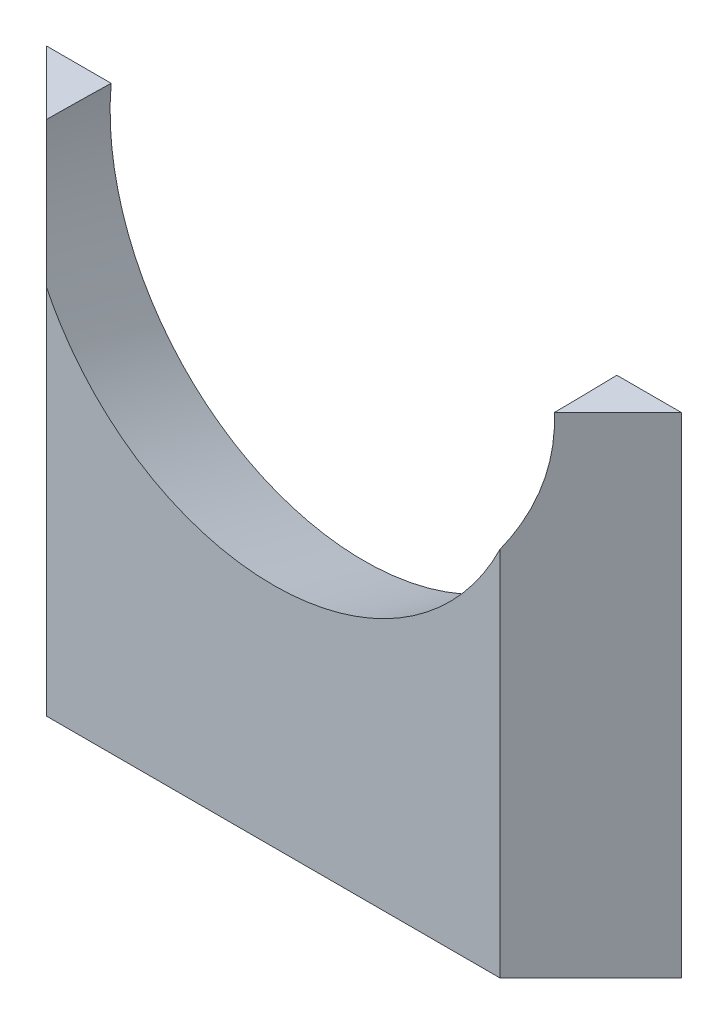
SolidWorks part; units mm, degrees
ref_plane "Front Plane" through (0, 0, 0) normal (0, 0, 1) x (1, 0, 0)
ref_plane "Top Plane" through (0, 0, 0) normal (0, 1, 0) x (1, 0, 0)
ref_plane "Right Plane" through (0, 0, 0) normal (1, 0, 0) x (0, 0, -1)
sketch "Sketch1" plane through (0, 0, 0) normal (0, 1, 0) x (1, 0, 0)
  line L0 (-17.5, 2.5) -> (17.5, 2.5)
  line L1 (17.5, 2.5) -> (12.5, -2.5)
  line L2 (12.5, -2.5) -> (-12.5, -2.5)
  line L3 (-12.5, -2.5) -> (-17.5, 2.5)
  line L4 (0, 2.5) -> (0, 0) construction
  line L5 (0, 0) -> (0, -2.5) construction
  dimension "D1" = 2.5
  dimension "D2" = 2.5
  dimension "D3" = 35
  dimension "D4" = 25
extrude "Boss-Extrude1" add sketch "Sketch1" along normal blind 27
ref_plane "Plane1" through (0, 0.625, 2.3325) normal (0, 0.2588, 0.9659) x (1, 0, 0)
sketch "Sketch2" plane through (0, 0.625, 2.3325) normal (0, 0.2588, 0.9659) x (1, 0, 0)
  line L0 (-12.5, 25.4329) -> (12.5, 25.4329) construction
  circle A0 centre (0, 25.4329) radius 14
  point P2 (0, 29.1101)
  dimension "D1" = 28
extrude "Cut-Extrude1" cut sketch "Sketch2" against normal through all both and the other way through all
